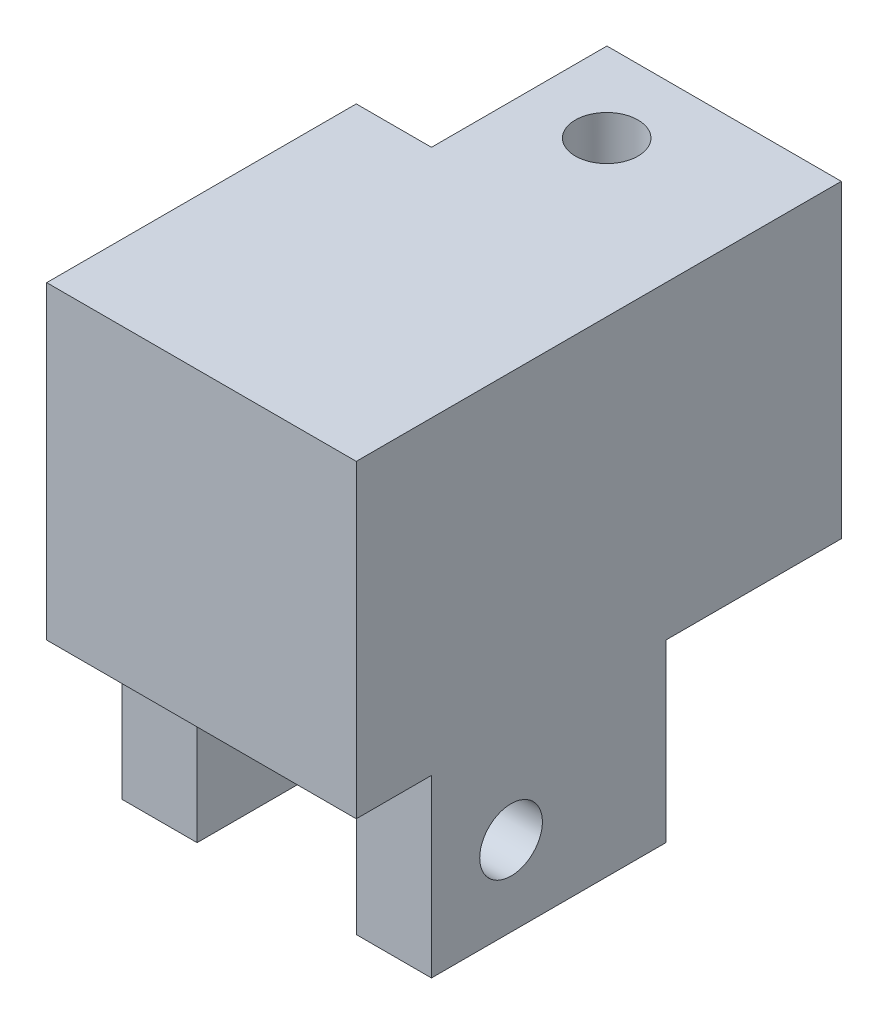
SolidWorks part; units mm, degrees
ref_plane "前视基准面" through (0, 0, 0) normal (0, 0, 1) x (1, 0, 0)
ref_plane "上视基准面" through (0, 0, 0) normal (0, 1, 0) x (1, 0, 0)
ref_plane "右视基准面" through (0, 0, 0) normal (1, 0, 0) x (0, 0, -1)
sketch "草图1" plane through (0, 0, 0) normal (0, 1, 0) x (1, 0, 0)
  line L1 (-6.35, -6.35) -> (6.35, -6.35)
  line L2 (-6.35, -6.35) -> (-6.35, 6.35)
  line L3 (-6.35, 6.35) -> (6.35, 6.35)
  line L4 (6.35, -6.35) -> (6.35, 6.35)
  line L5 (-6.35, -6.35) -> (6.35, 6.35) construction
  line L6 (-6.35, 6.35) -> (6.35, -6.35) construction
  line L7 (12.35, -12.35) -> (-12.35, -12.35)
  line L8 (12.35, -12.35) -> (12.35, 12.35)
  line L9 (12.35, 12.35) -> (-12.35, 12.35)
  line L10 (-12.35, -12.35) -> (-12.35, 12.35)
  line L11 (12.35, -12.35) -> (-12.35, 12.35) construction
  line L12 (12.35, 12.35) -> (-12.35, -12.35) construction
  point P0 (0, 0)
  point P6 (0, 0)
  dimension "D1" = 12.7
  dimension "D2" = 12.7
  dimension "D3" = 6
  dimension "D4" = 6
extrude "凸台-拉伸2" add sketch "草图1" along normal blind 24.7 contours L1 L4 L3 L2 | L10 L7 L8 L9 L4 L1 L2 L3
sketch "草图3" plane through (0, 0, 0) normal (0, -1, 0) x (1, 0, 0)
  line L0 (-6.35, 6.35) -> (-12.35, 6.35)
  line L1 (-6.35, -6.35) -> (6.35, -6.35)
  line L2 (-6.35, -6.35) -> (-6.35, 6.35)
  line L3 (-6.35, 6.35) -> (6.35, 6.35)
  line L4 (6.35, -6.35) -> (6.35, 6.35)
  line L5 (-6.35, -6.35) -> (6.35, 6.35) construction
  line L6 (-6.35, 6.35) -> (6.35, -6.35) construction
  line L8 (-12.35, 12.35) -> (-12.35, -12.35) construction
  line L9 (-12.35, 6.35) -> (-12.35, -12.35)
  line L10 (-12.35, -12.35) -> (12.35, -12.35)
  line L12 (12.35, -12.35) -> (12.35, 6.35)
  line L13 (12.35, 12.35) -> (12.35, -12.35) construction
  line L14 (12.35, 6.35) -> (6.35, 6.35)
  point P0 (0, 0)
  dimension "D1" = 12.7
  dimension "D2" = 12.7
extrude "凸台-拉伸3" add sketch "草图3" along normal blind 14
sketch "草图5" plane through (0, 0, -12.35) normal (0, 0, -1) x (-1, 0, 0)
  line L0 (12.35, 24.7) -> (12.35, -14) construction
  line L1 (-12.35, 24.7) -> (12.35, 24.7)
  line L2 (-12.35, 24.7) -> (-12.35, 0)
  line L3 (-12.35, 0) -> (12.35, 0)
  line L4 (12.35, 24.7) -> (12.35, 0)
  line L5 (-12.35, 12.35) -> (9.2794, 12.35) construction
  line L6 (0, 24.7) -> (0, 5.0247) construction
  line L7 (6.35, 18.7) -> (6.35, 24.7)
  line L8 (-6.35, 6) -> (6.35, 6)
  line L9 (-6.35, 6) -> (-6.35, 18.7)
  line L10 (-6.35, 18.7) -> (6.35, 18.7)
  line L11 (6.35, 6) -> (6.35, 18.7)
  line L12 (-6.35, 6) -> (6.35, 18.7) construction
  line L13 (-6.35, 18.7) -> (6.35, 6) construction
  line L14 (6.35, 24.7) -> (-12.35, 24.7)
  line L15 (-12.35, 0) -> (6.35, 0)
  line L16 (6.35, 0) -> (6.35, 6)
  point P12 (0, 12.35)
  line M9 (-12.35, 24.7) -> (-12.35, -14)
  dimension "D1" = 24.7
  dimension "D2" = 12.7
  dimension "D3" = 12.7
extrude "凸台-拉伸5" add sketch "草图5" along normal blind 14 contours L3 L16 L8 L9 L10 L7 L1 M9
sketch "草图6" plane through (0, 0, 0) normal (0, -1, 0) x (1, 0, 0)
  line L0 (-12.35, -12.35) -> (12.35, -12.35) construction
  line L1 (-6.35, -26.35) -> (-6.35, -12.35) construction
  circle A0 centre (0, -19.98) radius 2.5
  dimension "D3" = 5
  dimension "D1" = 7.63
  dimension "D2" = 6.35
extrude "切除-拉伸1" cut sketch "草图6" against normal through all
sketch "草图7" plane through (-12.35, 0, 0) normal (-1, 0, 0) x (0, 0, 1)
  line L0 (12.35, 0) -> (6.35, 0) construction
  line L1 (6.35, -14) -> (6.35, 0) construction
  circle A0 centre (0, -7.63) radius 2.5
  dimension "D2" = 5
  dimension "D1" = 7.63
  dimension "D3" = 6.35
extrude "切除-拉伸2" cut sketch "草图7" against normal through all
